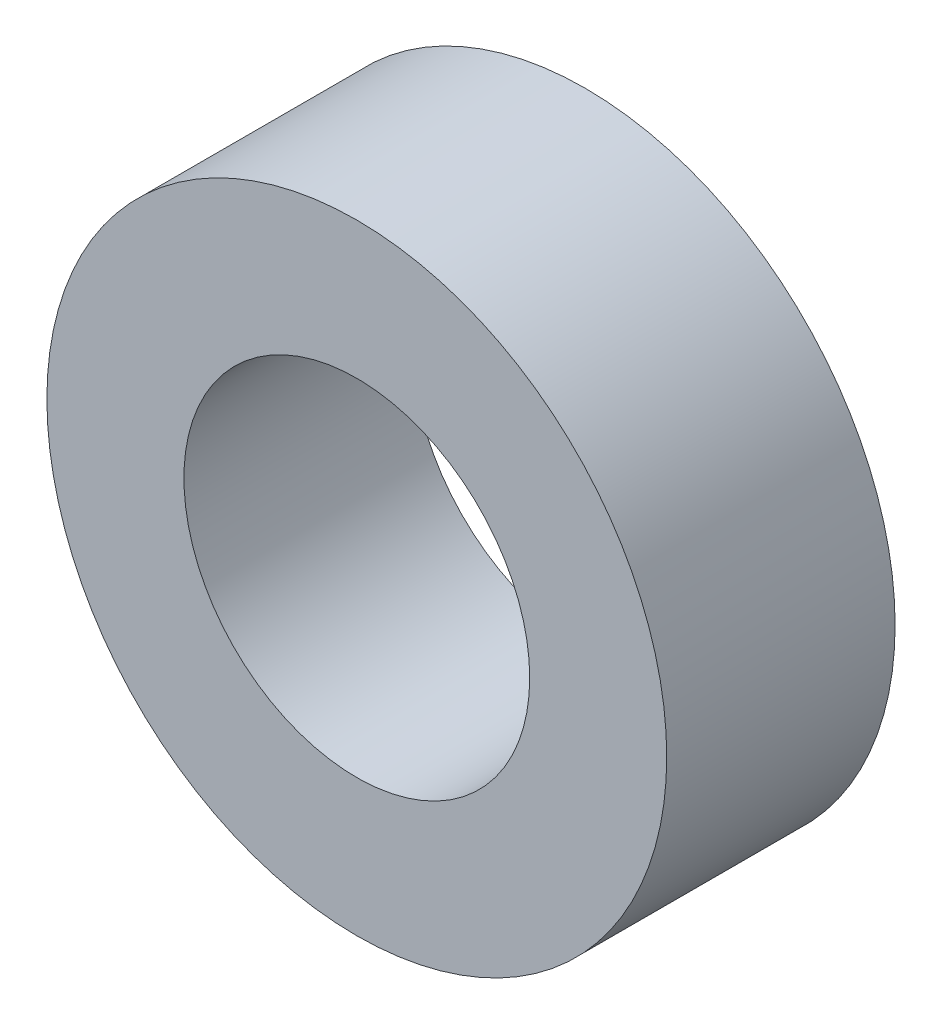
SolidWorks part; units mm, degrees
ref_plane "Alzado" through (0, 0, 0) normal (0, 0, 1) x (1, 0, 0)
ref_plane "Planta" through (0, 0, 0) normal (0, 1, 0) x (1, 0, 0)
ref_plane "Vista lateral" through (0, 0, 0) normal (1, 0, 0) x (0, 0, -1)
sketch "Croquis1" plane through (0, 0, 0) normal (0, 0, 1) x (1, 0, 0)
  circle A0 centre (0, 0) radius 5.3
  circle A1 centre (0, 0) radius 9.5
extrude "Saliente-Extruir1" add sketch "Croquis1" along normal blind 7
